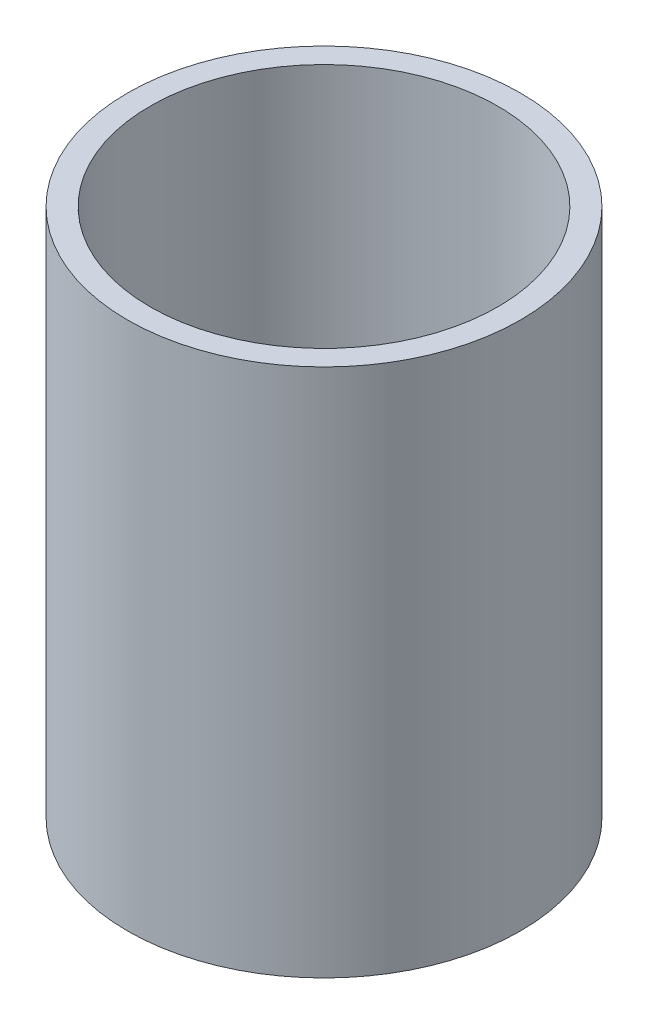
SolidWorks part; units mm, degrees
ref_plane "Front Plane" through (0, 0, 0) normal (0, 0, 1) x (1, 0, 0)
ref_plane "Top Plane" through (0, 0, 0) normal (0, 1, 0) x (1, 0, 0)
ref_plane "Right Plane" through (0, 0, 0) normal (1, 0, 0) x (0, 0, -1)
sketch "Sketch1" plane through (0, 0, 0) normal (0, 1, 0) x (1, 0, 0)
  circle A0 centre (0, 0) radius 26
  circle A1 centre (0, 0) radius 23
  dimension "D1" = 52
  dimension "D2" = 46
extrude "Boss-Extrude1" add sketch "Sketch1" along normal mid plane 70 contours A0 A1
